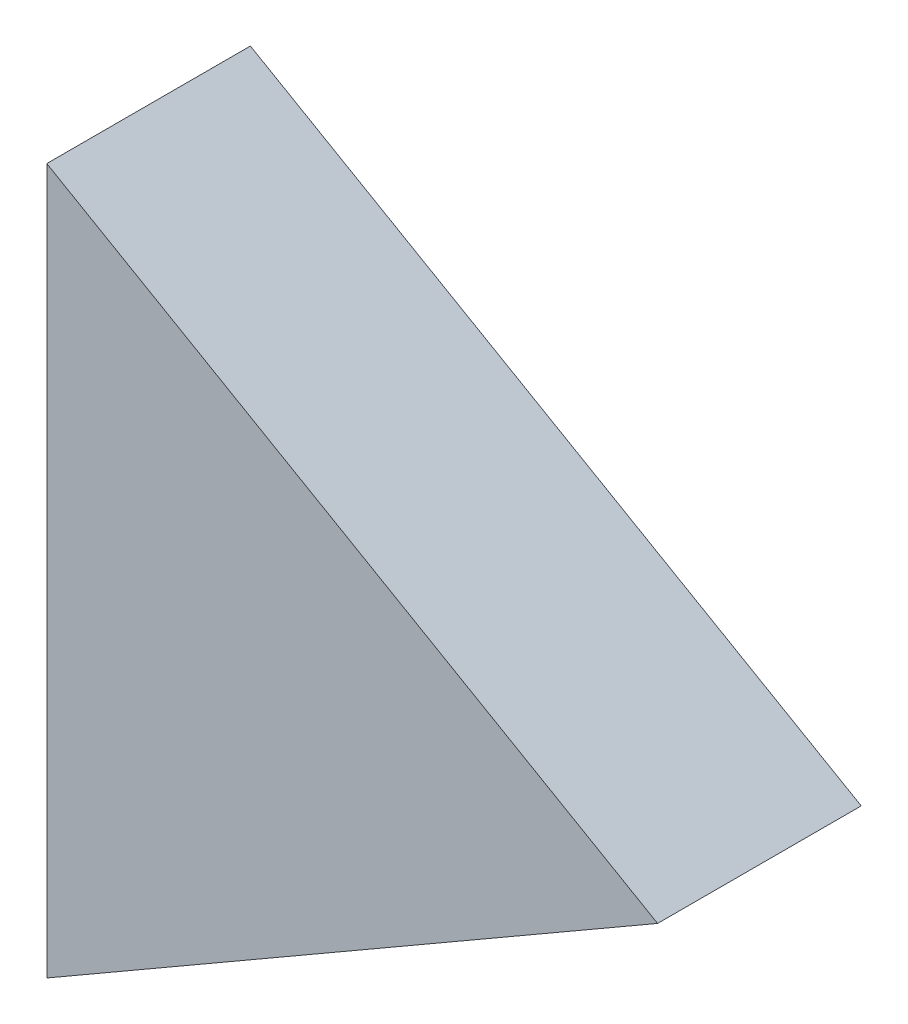
SolidWorks part; units mm, degrees
ref_plane "前视基准面" through (0, 0, 0) normal (0, 0, 1) x (1, 0, 0)
ref_plane "上视基准面" through (0, 0, 0) normal (0, 1, 0) x (1, 0, 0)
ref_plane "右视基准面" through (0, 0, 0) normal (1, 0, 0) x (0, 0, -1)
sketch "草图1" plane through (0, 0, 0) normal (0, 0, 1) x (1, 0, 0)
  line L1 (200, 0) -> (-100, 173.2051)
  line L2 (-100, 173.2051) -> (-100, -173.2051)
  line L3 (-100, -173.2051) -> (200, 0)
  circle A0 centre (0, 0) radius 100 construction
  dimension "D2" = 200
extrude "凸台-拉伸1" add sketch "草图1" along normal mid plane 100 contours L1 L2 L3
sketch "草图3" plane through (0, 0, 0) normal (0, 0, 1) x (1, 0, 0)
  line L1 (200, 0) -> (-100, 173.2051) construction
  point P3 (50, 86.6025)
